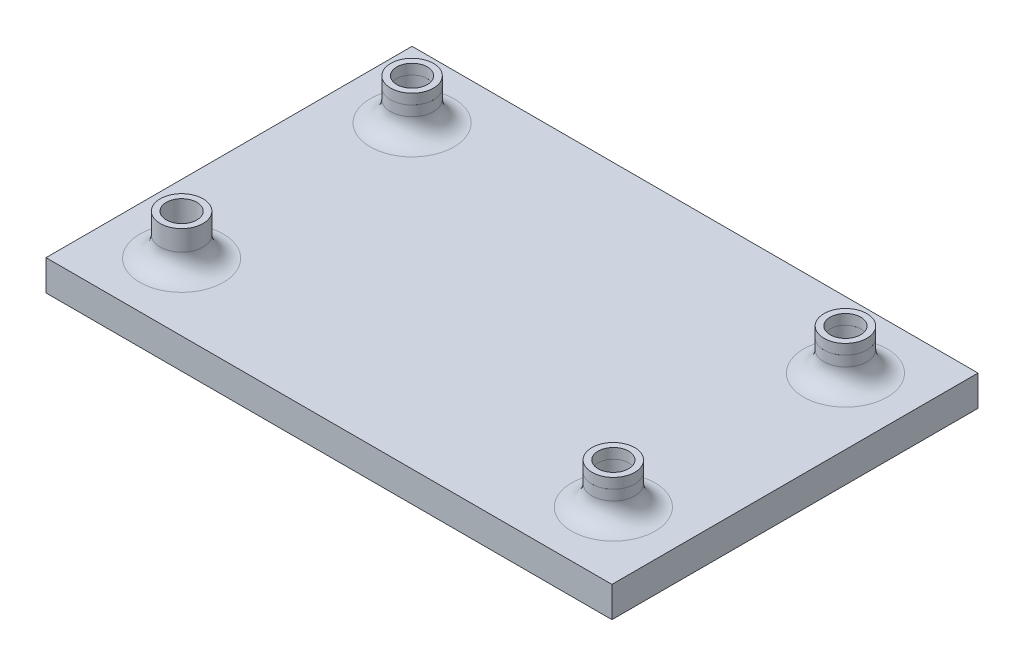
SolidWorks part; units mm, degrees
ref_plane "Front Plane" through (0, 0, 0) normal (0, 0, 1) x (1, 0, 0)
ref_plane "Top Plane" through (0, 0, 0) normal (0, 1, 0) x (1, 0, 0)
ref_plane "Right Plane" through (0, 0, 0) normal (1, 0, 0) x (0, 0, -1)
sketch "Sketch2" plane through (0, 0, 0) normal (0, 1, 0) x (1, 0, 0)
  line L2 (0, 0) -> (0, 35.433)
  line L16 (0, 35.433) -> (60.325, 35.433)
  line L22 (0, 0) -> (60.325, 0)
  line L28 (60.325, 35.433) -> (60.325, 0)
  circle A0 centre (57.15, 32.258) radius 1.905
  circle A1 centre (57.15, 3.3519) radius 1.905
  circle A2 centre (3.175, 32.258) radius 1.905
  circle A3 centre (3.429, 3.302) radius 1.905
  point P5 (0, 0)
  point P6 (0, 0)
  point P7 (60.5168, 50.3978)
  dimension "D7" = 3.175
  dimension "D13" = 3.81
  dimension "D5" = 3.81
  dimension "D6" = 3.81
  dimension "D14" = 3.81
  dimension "D2" = 60.325
  dimension "D3" = 3.175
  dimension "D4" = 3.175
  dimension "D8" = 3.302
  dimension "D9" = 3.429
  dimension "D10" = 3.3519
  dimension "D11" = 3.175
  dimension "D12" = 3.175
  dimension "D15" = 35.433
extrude "Boss-Extrude1" add sketch "Sketch2" along normal blind 3.81
sketch "Sketch4" plane through (0, 3.81, 0) normal (0, 1, 0) x (1, 0, 0)
  circle A0 centre (3.175, 32.258) radius 2.667
  circle A1 centre (57.15, 32.258) radius 2.667
  circle A2 centre (57.15, 3.3519) radius 2.667
  circle A3 centre (3.429, 3.302) radius 2.667
  circle A4 centre (3.175, 32.258) radius 1.905
  circle A5 centre (57.15, 32.258) radius 1.905
  circle A6 centre (57.15, 3.3519) radius 1.905
  circle A7 centre (3.429, 3.302) radius 1.905
  dimension "D1" = 5.334
  dimension "D2" = 5.334
  dimension "D3" = 5.334
  dimension "D4" = 5.334
  dimension "D5" = 3.81
  dimension "D6" = 3.81
  dimension "D7" = 3.81
  dimension "D8" = 3.81
extrude "Boss-Extrude3" add sketch "Sketch4" along normal blind 3.81 separate body
sketch "Sketch6" plane through (0, 7.62, 0) normal (0, 1, 0) x (1, 0, 0)
  circle A0 centre (3.429, 3.302) radius 1.905
  circle A1 centre (3.429, 3.302) radius 2.667
  circle A2 centre (3.175, 32.258) radius 1.905
  circle A3 centre (3.175, 32.258) radius 2.667
  circle A4 centre (57.15, 3.3519) radius 1.905
  circle A5 centre (57.15, 32.258) radius 1.905
  circle A6 centre (57.15, 32.258) radius 2.667
  circle A7 centre (57.15, 3.3519) radius 2.667
  dimension "D1" = 3.81
  dimension "D2" = 5.334
  dimension "D3" = 5.334
  dimension "D4" = 3.81
  dimension "D5" = 3.81
  dimension "D6" = 5.334
  dimension "D7" = 3.81
  dimension "D8" = 5.334
extrude "Boss-Extrude4" add sketch "Sketch6" along normal blind 1.27
sketch "Sketch7" plane through (0, 3.81, 0) normal (0, 1, 0) x (1, 0, 0)
  line L1 (-5.08, 40.513) -> (65.405, 40.513)
  line L2 (0, 0) -> (60.325, 0) construction
  line L4 (-5.08, 40.513) -> (-5.08, -5.08)
  line L5 (-5.08, -5.08) -> (65.405, -5.08)
  line L6 (65.405, 40.513) -> (65.405, -5.08)
  line L7 (0, 35.433) -> (0, 0) construction
  line L8 (60.325, 0) -> (60.325, 35.433) construction
  line L10 (0, 35.433) -> (60.325, 35.433)
  line L11 (0, 35.433) -> (0, 0)
  line L12 (0, 0) -> (60.325, 0)
  line L13 (60.325, 35.433) -> (60.325, 0)
  dimension "D1" = 5.08
  dimension "D2" = 5.08
  dimension "D3" = 5.08
  dimension "D4" = 5.08
extrude "Boss-Extrude5" add sketch "Sketch7" against normal up to surface (3.81 mm away) up to face at (3.175, 0, -30.353)
fillet "Fillet5" radius 2.54 1 edges at (3.175, 3.81, -34.925)
fillet "Fillet7" radius 2.54 1 edges at (3.429, 3.81, -5.969)
fillet "Fillet8" radius 2.54 1 edges at (57.15, 3.81, -6.0189)
fillet "Fillet9" radius 2.54 1 edges at (57.15, 3.81, -34.925)
